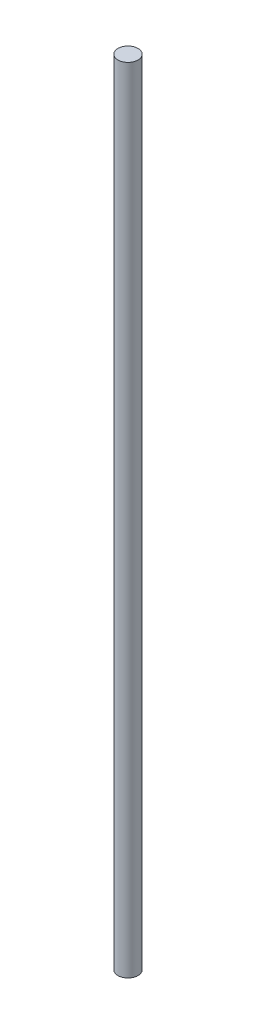
SolidWorks part; units mm, degrees
ref_plane "Front Plane" through (0, 0, 0) normal (0, 0, 1) x (1, 0, 0)
ref_plane "Top Plane" through (0, 0, 0) normal (0, 1, 0) x (1, 0, 0)
ref_plane "Right Plane" through (0, 0, 0) normal (1, 0, 0) x (0, 0, -1)
sketch "Sketch1" plane through (0, 0, 0) normal (0, 1, 0) x (1, 0, 0)
  circle A0 centre (0, 0) radius 2.413
  dimension "D1" = 4.826
extrude "Boss-Extrude1" add sketch "Sketch1" along normal blind 190.5
